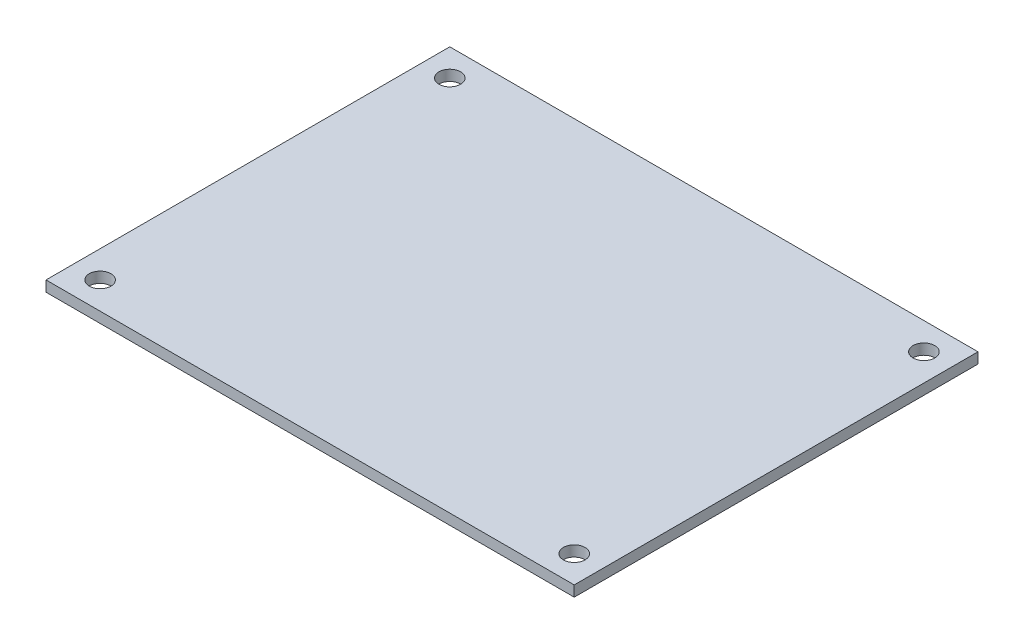
SolidWorks part; units mm, degrees
ref_plane "Front Plane" through (0, 0, 0) normal (0, 0, 1) x (1, 0, 0)
ref_plane "Top Plane" through (0, 0, 0) normal (0, 1, 0) x (1, 0, 0)
ref_plane "Right Plane" through (0, 0, 0) normal (1, 0, 0) x (0, 0, -1)
sketch "Sketch1" plane through (0, 0, 0) normal (0, 1, 0) x (1, 0, 0)
  line L0 (-44.515, 37.91) -> (-44.515, 32.83) construction
  line L1 (-49.595, -37.91) -> (49.595, -37.91)
  line L2 (-49.595, -37.91) -> (-49.595, 37.91)
  line L3 (-49.595, 37.91) -> (49.595, 37.91)
  line L4 (49.595, -37.91) -> (49.595, 37.91)
  line L5 (-49.595, -37.91) -> (49.595, 37.91) construction
  line L6 (-49.595, 37.91) -> (49.595, -37.91) construction
  line L7 (-44.515, 32.83) -> (-49.595, 32.83) construction
  line L8 (44.515, -32.83) -> (49.595, -32.83) construction
  line L9 (44.515, -32.83) -> (44.515, -37.91) construction
  circle A1 centre (-44.515, -32.83) radius 2.032
  circle A2 centre (44.515, -32.83) radius 2.032
  circle A3 centre (44.515, 32.83) radius 2.032
  circle A4 centre (-44.515, 32.83) radius 2.032
  point P0 (0, 0)
  point P16 (0, 0)
  dimension "PCB hole diameter" = 4.064
  dimension "PCB hole position" = 5.08
  dimension "PCB width" = 99.19
  dimension "PCB height" = 75.82
extrude "Boss-Extrude1" add sketch "Sketch1" along normal blind 2
equation "\"tolerance\"= 0"
equation "\"PCB hole diameter@Sketch1\"= 4.064mm + \"tolerance\""
equation "\"PCB hole position@Sketch1\"= 5.08mm + \"tolerance\""
equation "\"PCB width@Sketch1\"=99.19mm+\"tolerance\""
equation "\"PCB height@Sketch1\"=75.82mm+\"tolerance\""
equation "\"PCB depth@Boss-Extrude1\"=2mm-\"tolerance\""
